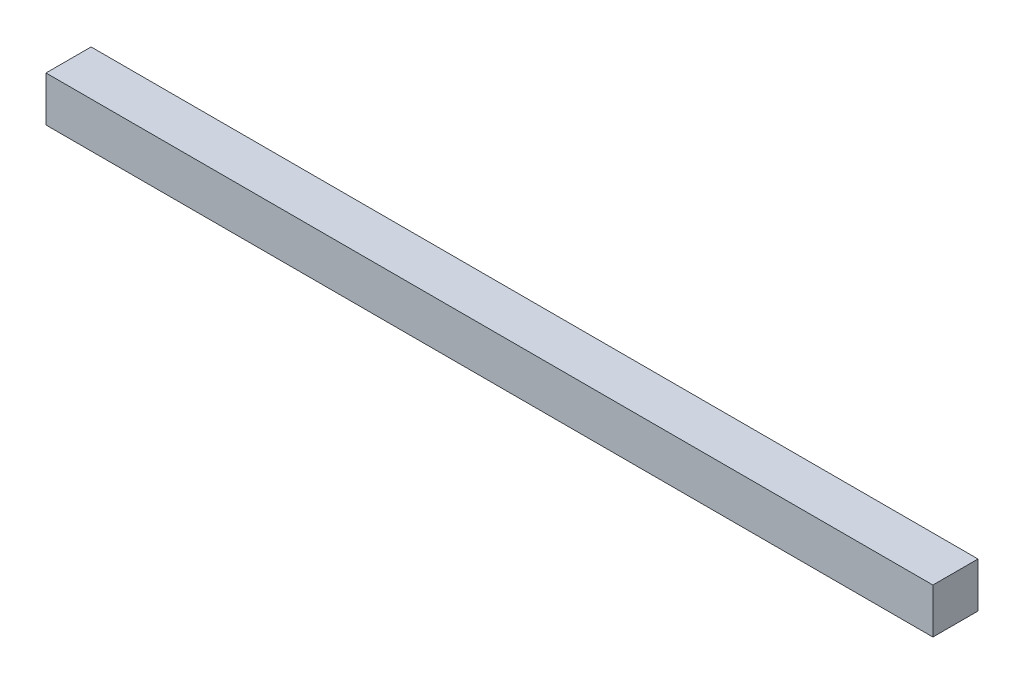
SolidWorks part; units mm, degrees
ref_plane "Front Plane" through (0, 0, 0) normal (0, 0, 1) x (1, 0, 0)
ref_plane "Top Plane" through (0, 0, 0) normal (0, 1, 0) x (1, 0, 0)
ref_plane "Right Plane" through (0, 0, 0) normal (1, 0, 0) x (0, 0, -1)
sketch "Sketch1" plane through (0, 0, 0) normal (0, 1, 0) x (1, 0, 0)
  line L1 (0, 0) -> (590, 0)
  line L2 (0, 0) -> (0, 30)
  line L3 (0, 30) -> (590, 30)
  line L4 (590, 0) -> (590, 30)
  dimension "D1" = 30
  dimension "D2" = 590
extrude "Boss-Extrude1" add sketch "Sketch1" along normal blind 30
